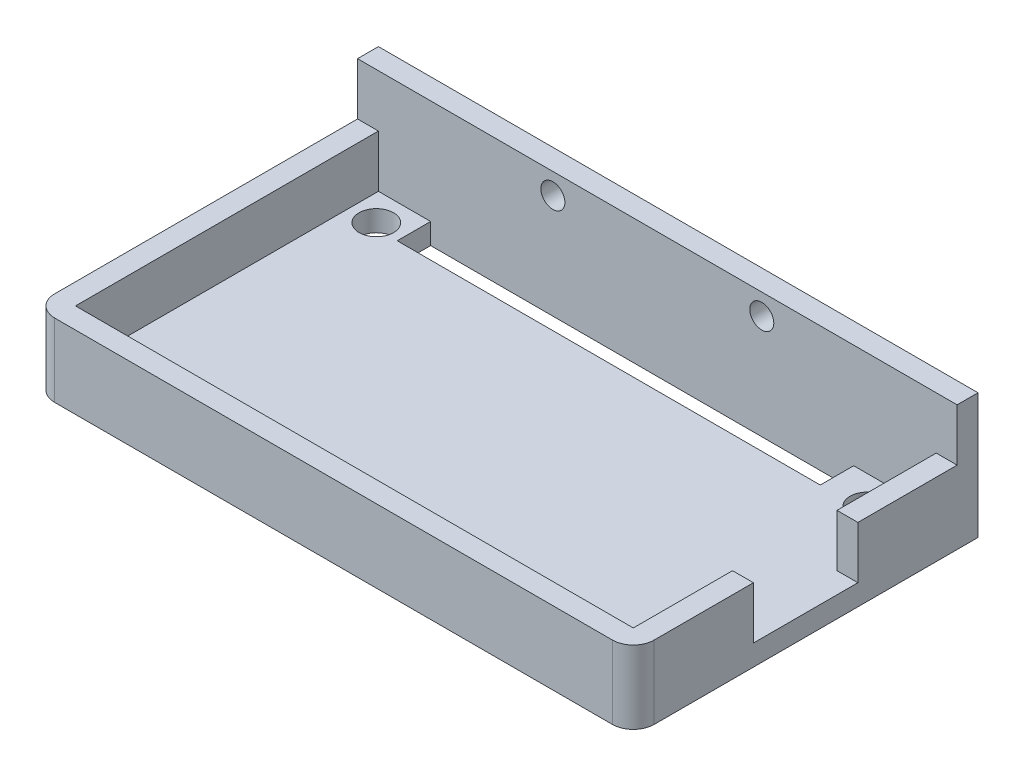
SolidWorks part; units mm, degrees
ref_plane "Front Plane" through (0, 0, 0) normal (0, 0, 1) x (1, 0, 0)
ref_plane "Top Plane" through (0, 0, 0) normal (0, 1, 0) x (1, 0, 0)
ref_plane "Right Plane" through (0, 0, 0) normal (1, 0, 0) x (0, 0, -1)
sketch "Sketch1" plane through (0, 0, 0) normal (0, 1, 0) x (1, 0, 0)
  line L1 (0, 0) -> (57.4, 0)
  line L2 (0, 0) -> (0, 33)
  line L3 (0, 33) -> (57.4, 33)
  line L4 (57.4, 0) -> (57.4, 33)
  dimension "D1" = 57.4
  dimension "D2" = 33
extrude "Boss-Extrude1" add sketch "Sketch1" along normal blind 7
shell "Shell3" thickness 2
sketch "Sketch2" plane through (0, 2, 0) normal (0, 1, 0) x (1, 0, 0)
  line L0 (4.5, 28.3) -> (4.5, 4.7) construction
  line L1 (2, 2) -> (2, 31) construction
  line L2 (2, 31) -> (2, 2) construction
  circle A0 centre (4.5, 28.3) radius 1.65
  circle A1 centre (51.5, 28.3) radius 1.65
  circle A2 centre (4.5, 4.7) radius 1.65
  circle A3 centre (51.5, 4.7) radius 1.65
  point P10 (2, 16.5)
  point P11 (4.5, 16.5)
  dimension "D1" = 3.3
  dimension "D2" = 47
  dimension "D3" = 23.6
  dimension "D4" = 2.5
extrude "Cut-Extrude1" cut sketch "Sketch2" against normal through all
sketch "Sketch3" plane through (0, 2, 0) normal (0, 1, 0) x (1, 0, 0)
  line L0 (55.4, 31) -> (2, 31) construction
  line L1 (7, 31) -> (47.5, 31)
  line L2 (7, 31) -> (7, 27.8)
  line L3 (7, 27.8) -> (47.5, 27.8)
  line L4 (47.5, 31) -> (47.5, 27.8)
  line L5 (2, 31) -> (2, 2) construction
  line L6 (2, 16.5) -> (55.4, 16.5) construction
  line L7 (55.4, 2) -> (55.4, 31) construction
  line L8 (47.5, 2) -> (47.5, 5.2)
  line L9 (7, 5.2) -> (47.5, 5.2)
  line L10 (7, 2) -> (7, 5.2)
  line L11 (7, 2) -> (47.5, 2)
  circle A0 centre (51.5, 28.3) radius 1.65 construction
  dimension "D1" = 5
  dimension "D2" = 4
  dimension "D3" = 3.2
extrude "Cut-Extrude2" cut sketch "Sketch3" against normal through all
sketch "Sketch4" plane through (0, 7, 0) normal (0, 1, 0) x (1, 0, 0)
  line L0 (55.4, 2) -> (55.4, 31) construction
  line L1 (55.4, 21.5) -> (57.4, 21.5)
  line L2 (55.4, 21.5) -> (55.4, 11.5)
  line L3 (55.4, 11.5) -> (57.4, 11.5)
  line L4 (57.4, 21.5) -> (57.4, 11.5)
  line L5 (57.4, 0) -> (57.4, 33) construction
  point P8 (57.4, 16.5)
  point P9 (57.4, 16.5)
  dimension "D1" = 10
extrude "Cut-Extrude3" cut sketch "Sketch4" against normal up to surface (5 mm away) up to face at (51.5, 2, -26.65)
sketch "Sketch5" plane through (0, 7, 0) normal (0, 1, 0) x (1, 0, 0)
  line L0 (57.4, 21.5) -> (57.4, 33) construction
  line L1 (0, 33) -> (57.4, 33)
  line L2 (0, 33) -> (0, 31)
  line L3 (0, 31) -> (57.4, 31)
  line L4 (57.4, 33) -> (57.4, 31)
  line L5 (55.4, 31) -> (47.5, 31) construction
extrude "Boss-Extrude2" add sketch "Sketch5" along normal blind 5
sketch "Sketch6" plane through (0, 0, -33) normal (0, 0, -1) x (-1, 0, 0)
  line L0 (-38.7, 10) -> (-18.7, 10) construction
  line L3 (-57.4, 12) -> (0, 12) construction
  circle A0 centre (-38.7, 10) radius 1.15
  circle A1 centre (-18.7, 10) radius 1.15
  point P5 (-28.7, 10)
  point P8 (-28.7, 12)
  dimension "D1" = 2.3
  dimension "D2" = 2.3
  dimension "D3" = 2
  dimension "D4" = 20
extrude "Cut-Extrude4" cut sketch "Sketch6" against normal up to next
fillet "Fillet1" radius 2 2 edges at (0, 3.5, 0) (57.4, 3.5, 0)
